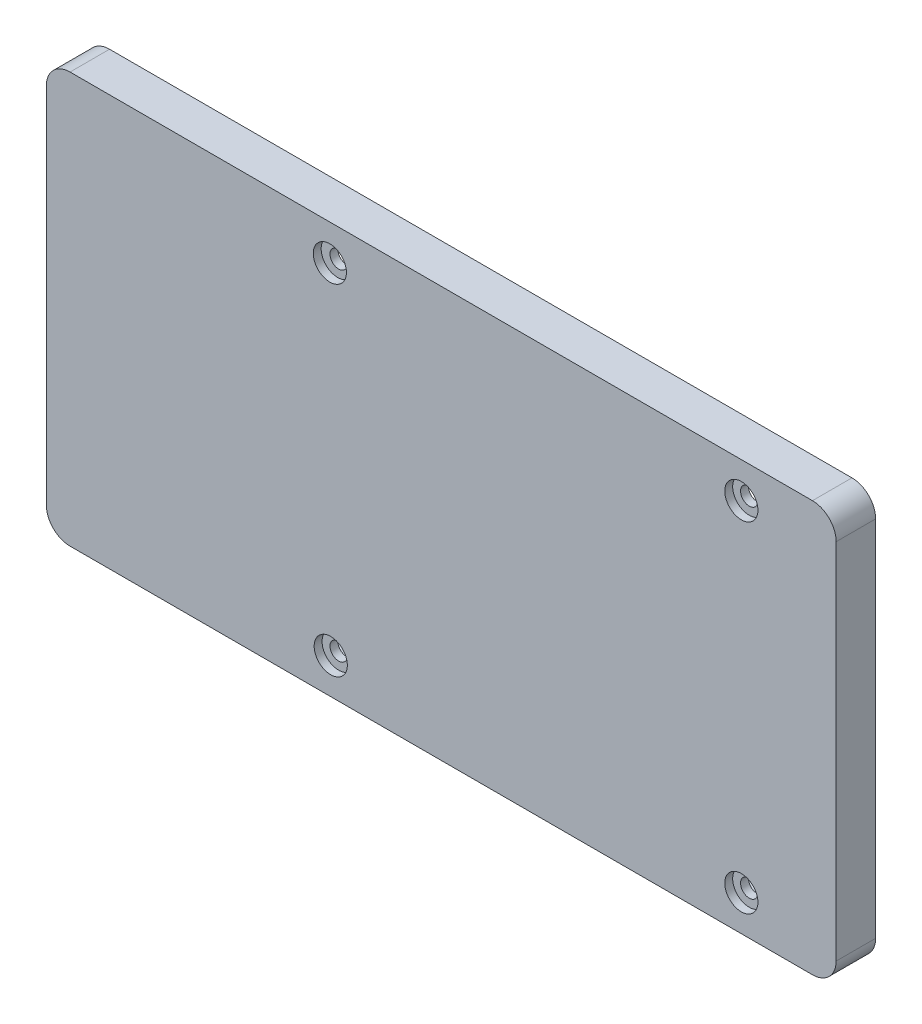
SolidWorks part; units mm, degrees
ref_plane "Front Plane" through (0, 0, 0) normal (0, 0, 1) x (1, 0, 0)
ref_plane "Top Plane" through (0, 0, 0) normal (0, 1, 0) x (1, 0, 0)
ref_plane "Right Plane" through (0, 0, 0) normal (1, 0, 0) x (0, 0, -1)
other "Configuration Table"
sketch "草图1" plane through (0, 0, 1066.8856) normal (0, 0, 1) x (1, 0, 0)
  line L0 (884.4138, 1043.1445) -> (884.4138, 997.1444) construction
  line L1 (884.4138, 1046.1318) -> (984.3886, 1046.1318)
  line L2 (884.4138, 1046.1318) -> (884.4138, 994.1571)
  line L3 (884.4138, 994.1571) -> (984.3886, 994.1571)
  line L4 (984.3886, 1046.1318) -> (984.3886, 994.1571)
  line L5 (887.4011, 994.1571) -> (981.4013, 994.1571) construction
  line L6 (984.3886, 997.1444) -> (984.3886, 1043.1445) construction
  line L7 (981.4013, 1046.1318) -> (887.4011, 1046.1318) construction
extrude "凸台-拉伸1" add sketch "草图1" along normal blind 5
sketch "草图2" plane through (0, 0, 1066.8856) normal (0, 0, -1) x (-1, 0, 0)
  line L0 (-884.4138, 1046.1318) -> (-884.4138, 994.1571) construction
  line L1 (-982.8886, 1044.388) -> (-885.9138, 1044.388)
  line L2 (-982.8886, 1044.388) -> (-982.8886, 995.6571)
  line L3 (-982.8886, 995.6571) -> (-885.9138, 995.6571)
  line L4 (-885.9138, 1044.388) -> (-885.9138, 995.6571)
  line L5 (-981.4013, 1045.888) -> (-887.4011, 1045.888) construction
  line L6 (-884.4138, 994.1571) -> (-984.3886, 994.1571) construction
  line L7 (-984.3886, 994.1571) -> (-984.3886, 1046.1318) construction
  dimension "D1" = 1.5
  dimension "D2" = 1.5
  dimension "D3" = 1.5
  dimension "D4" = 1.5
extrude "切除-拉伸1" cut sketch "草图2" against normal blind 3
sketch "草图3" plane through (0, 0, 1071.8856) normal (0, 0, 1) x (1, 0, 0)
  line L0 (984.3886, 994.1571) -> (984.3886, 1046.1318) construction
  line L1 (984.3886, 1046.1318) -> (884.4138, 1046.1318) construction
  line L2 (884.4138, 994.1571) -> (984.3886, 994.1571) construction
  line L3 (884.4138, 1046.1318) -> (884.4138, 994.1571) construction
  circle A0 centre (972.3886, 1041.6318) radius 1.1
  circle A1 centre (972.3886, 998.6571) radius 1.1
  circle A2 centre (920.4138, 998.6571) radius 1.1
  circle A3 centre (920.4138, 1041.6318) radius 1.1
  dimension "D1" = 12
  dimension "D2" = 4.5
  dimension "D3" = 4.5
  dimension "D4" = 12
  dimension "D5" = 4.5
  dimension "D6" = 36
  dimension "D7" = 36
  dimension "D8" = 4.5
extrude "切除-拉伸2" cut sketch "草图3" against normal through all
fillet "圆角1" radius 3 4 edges at (884.4138, 994.1571, 1069.3856) (984.3886, 994.1571, 1069.3856) (984.3886, 1046.1318, 1069.3856) (884.4138, 1046.1318, 1069.3856)
fillet "圆角2" radius 2 4 edges at (982.8886, 1044.388, 1068.3856) (885.9138, 1044.388, 1068.3856) (885.9138, 995.6571, 1068.3856) (982.8886, 995.6571, 1068.3856)
sketch "草图4" plane through (0, 0, 1071.8856) normal (0, 0, 1) x (1, 0, 0)
  circle A0 centre (920.2995, 1041.6445) radius 2.1
  circle A1 centre (972.3886, 1041.6318) radius 2.1
  circle A2 centre (972.3886, 998.6571) radius 2.1
  circle A3 centre (920.4138, 998.6571) radius 2.1
extrude "切除-拉伸3" cut sketch "草图4" against normal blind 1
